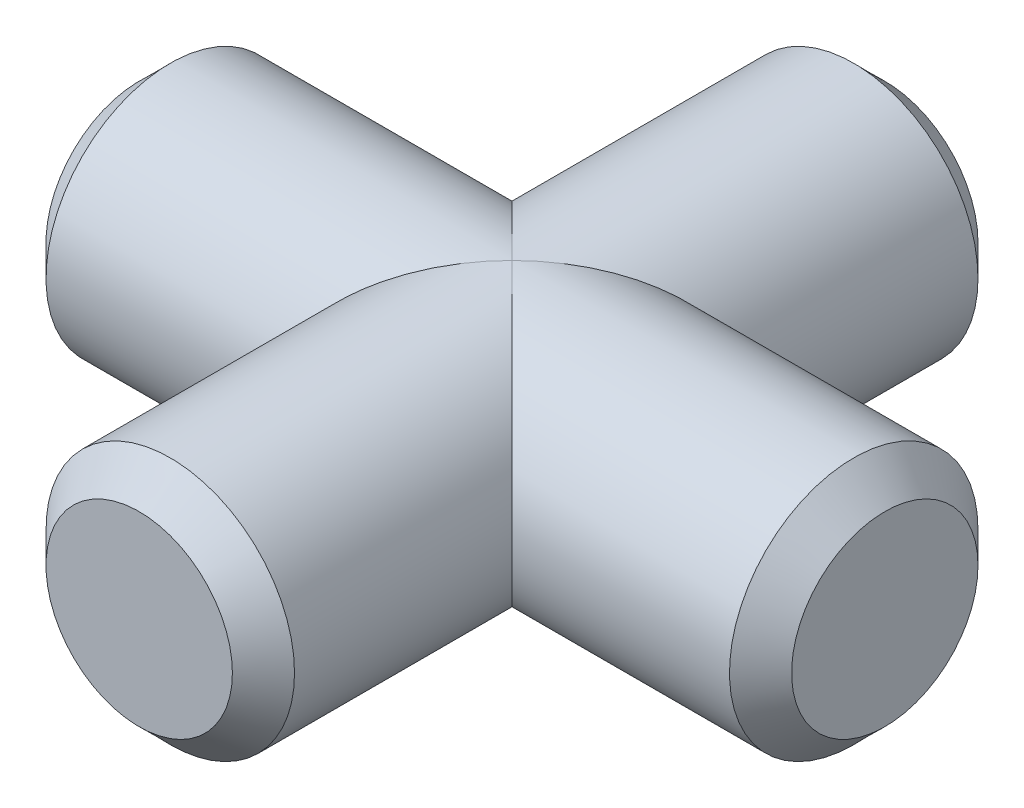
SolidWorks part; units mm, degrees
ref_plane "Front Plane" through (0, 0, 0) normal (0, 0, 1) x (1, 0, 0)
ref_plane "Top Plane" through (0, 0, 0) normal (0, 1, 0) x (1, 0, 0)
ref_plane "Right Plane" through (0, 0, 0) normal (1, 0, 0) x (0, 0, -1)
sketch "Sketch1" plane through (0, 0, 0) normal (0, 0, 1) x (1, 0, 0)
  circle A0 centre (0, 0) radius 2
  dimension "D1" = 4
extrude "Boss-Extrude1" add sketch "Sketch1" along normal blind 12
sketch "Sketch3" plane through (0, 0, 0) normal (1, 0, 0) x (0, 0, -1)
  line L0 (0, 0) -> (-12, 0) construction
  line L1 (0, -2) -> (0, 2) construction
  line L2 (-12, 2) -> (-12, -2) construction
  line L3 (-6, 0) -> (-6, 2) construction
  line L4 (0, 2) -> (-12, 2) construction
  line L5 (-6, 0) -> (-6, -2) construction
  line L6 (-12, -2) -> (0, -2) construction
  circle A0 centre (-6, 0) radius 2
  dimension "D1" = 4
extrude "Boss-Extrude2" add sketch "Sketch3" along normal mid plane 12
chamfer "Chamfer1" distance 0.5 angle 45 1 edges at (6, 0, 4)
chamfer "Chamfer2" distance 0.5 angle 45 3 edges at (-6, 0, 4) (2, 0, 12) (2, 0, 0)
